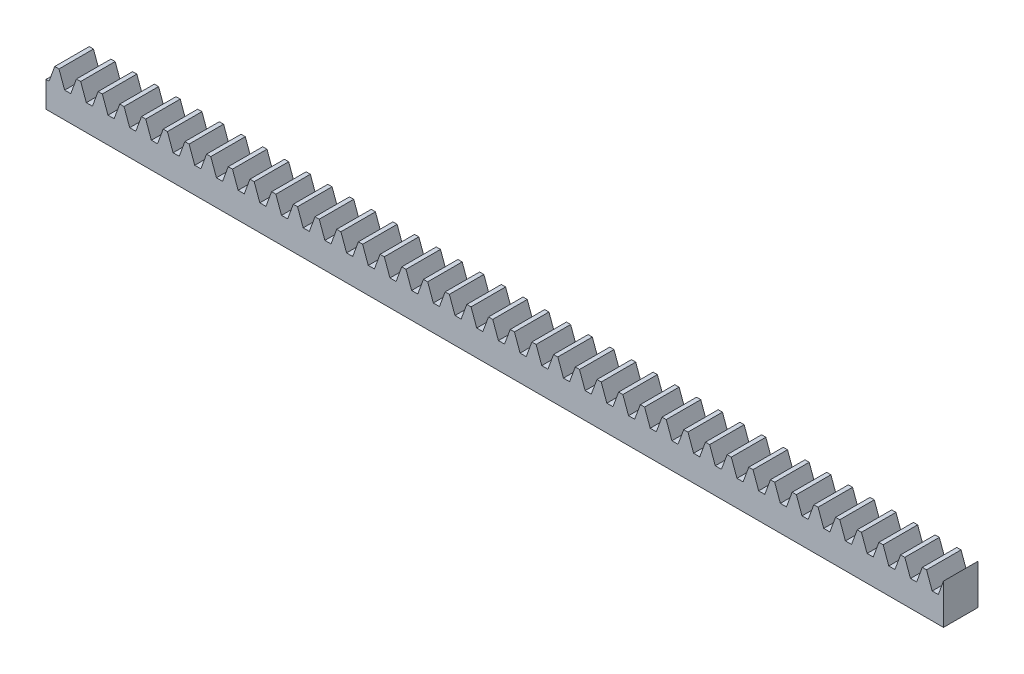
SolidWorks part; units mm, degrees
extrude "Blank" add sketch "BlankSke" against normal blind 5
sketch "BlankSke" plane through (0, 0, 0) normal (0, 0, 1) x (1, 0, 0)
  line L1 (0, 0) -> (130, 0)
  line L2 (0, 0) -> (0, 6)
  line L3 (0, 6) -> (130, 6)
  line L4 (130, 0) -> (130, 6)
  dimension "Length" = 130
  dimension "Blank_height" = 6
ref_plane "Plane1" through (0, 0, 0) normal (0, 0, 1) x (1, 0, 0)
ref_plane "Plane2" through (0, 0, 0) normal (0, 1, 0) x (1, 0, 0)
ref_plane "Plane3" through (0, 0, 0) normal (1, 0, 0) x (0, 0, -1)
sketch "HoldingSke" plane through (0, 0, 0) normal (0, 1, 0) x (1, 0, 0)
  line L0 (0, 0) -> (0.1392, 0.9903)
  line L1 (-15, 0) -> (100, 0) construction
  line L2 (0, 0) -> (-2.1039, 2.3779)
  line L3 (0, 0) -> (-11.863, 4.5341)
  line L4 (0, 0) -> (6.316, 5.8897)
  line L5 (0, 0) -> (-23.7986, -8.8762)
  line L6 (0, 0) -> (-10.5278, -7.1032)
  line L9 (-71.009, 38.7566) -> (51.1511, 83.2192)
  line L10 (-76.2, 3.3779) -> (-71.2, 3.3779)
  line L11 (0, 0) -> (-5, 0)
  line L12 (-76.2, 101.6) -> (-76.162, 101.6)
  line L13 (24.9733, 27.94) -> (52.9518, 28.4284)
  line L14 (24.9733, 27.94) -> (24.9743, 27.94)
  line L15 (24.9733, 27.94) -> (100.4006, 29.5858)
  circle A0 centre (0, 0) radius 19.05
  circle A1 centre (0, 0) radius 2.5
  circle A2 centre (0, 0) radius 12.7
  dimension "MPH" = 5
  dimension "Diameter" = 38.1
  dimension "Num_teeth" = 43
  dimension "Pitch" = 1
  dimension "Show_teeth" = 998
  dimension "Thickness" = 12.7
  dimension "Ap" = 20
  dimension "Pitch_height" = 5
  dimension "Width" = 5
  dimension "Backlash" = 0.038
  dimension "Addendum_fac" = 1
  dimension "Dedendum_fac" = 1.25
  dimension "Clearance_fac" = 0.25
  dimension "Dedendum_add" = 0.001
  dimension "Length" = 130
  dimension "Module" = 1
sketch "TooCutSkeIll" plane through (0, 0, 0) normal (0, 0, 1) x (1, 0, 0)
  line L0 (-1.2538, 5.9737) -> (-0.5045, 3.9152)
  line L1 (-0.2687, 3.75) -> (0.2687, 3.75)
  line L2 (0.5045, 3.9152) -> (1.2538, 5.9737)
  line L3 (130, 6) -> (0, 6) construction
  line L4 (0, 0) -> (0, 64.897) construction
  line L5 (-13.208, 5) -> (12.954, 5) construction
  line L6 (0, 0) -> (130, 0) construction
  line L7 (0.8994, 5) -> (0.8994, 48.7463) construction
  line L8 (-0.8994, 5) -> (-0.8994, 48.7463) construction
  line L9 (1.2914, 6) -> (1.2914, 6.0254)
  line L10 (-1.2914, 6) -> (-1.2914, 6.0254)
  line L11 (-1.2914, 6.0254) -> (1.2914, 6.0254)
  arc A0 (0.2687, 3.75) -> (0.5045, 3.9152) centre (0.2687, 4.001) ccw
  arc A1 (-0.5045, 3.9152) -> (-0.2687, 3.75) centre (-0.2687, 4.001) ccw
  arc A2 (1.2914, 6) -> (1.2538, 5.9737) centre (1.2914, 5.96) ccw
  arc A3 (-1.2538, 5.9737) -> (-1.2914, 6) centre (-1.2914, 5.96) ccw
  dimension "Pitch_height" = 5
  dimension "Addendum_plus" = 1.0254
  dimension "Pressure_angle" = 20
  dimension "Gap_width" = 1.7988
  dimension "Dedendum" = 1.25
extrude "ToothCutIll" [suppressed] cut sketch "TooCutSkeIll" against normal through all
sketch "TooCutSkeSim" plane through (0, 0, 0) normal (0, 0, 1) x (1, 0, 0)
  line L0 (0.4444, 3.75) -> (-0.4444, 3.75)
  line L1 (1.2726, 6.0254) -> (0.4444, 3.75)
  line L2 (0, 17.4625) -> (0, 53.467) construction
  line L3 (1.2726, 6.0254) -> (-1.2726, 6.0254)
  line L6 (-1.2726, 6.0254) -> (-0.4444, 3.75)
  line L9 (-0.8994, 5) -> (0.8994, 5) construction
  line L10 (0, 0) -> (130, 0) construction
  line L11 (0.8994, 5) -> (0.8994, 53.467) construction
  line L12 (-0.8994, 5) -> (-0.8994, 53.467) construction
  dimension "Pitch_height" = 5
  dimension "Addendum_plus" = 1.0254
  dimension "Pressure_angle" = 20
  dimension "Gap_width" = 1.7988
  dimension "Dedendum" = 1.25
extrude "ToothCutSim" cut sketch "TooCutSkeSim" against normal through all
pattern_linear "TeethCuts" count 42 spacing 3.1416 along (1, 0, 0) of "ToothCutIll", "ToothCutSim"
equation "' \"Module@HoldingSke\" = 6.35"
equation "' \"Num_teeth@HoldingSke\" = 12"
equation "' \"Ap@HoldingSke\" =  20"
equation "' \"Ap@HoldingSke\" = 20"
equation "' \"Width@HoldingSke\" = 0.25 * 25.4"
equation "' \"Show_teeth@HoldingSke\" = 500"
equation "' \"Backlash@HoldingSke\" = 0.009 * 25.4"
equation "' \"Addendum_fac@HoldingSke\" = 1.0"
equation "' \"Dedendum_fac@HoldingSke\" = 1.25"
equation "' \"Dedendum_add@HoldingSke\" = 0.00005 * 25.4"
equation "' \"Clearance_fac@HoldingSke\" = 0.25"
equation "' \"Pitch_height@HoldingSke\" = 1 * 25.4"
equation "' \"Length@HoldingSke\" = 4.71 * 25.4"
equation "\"Pitch@HoldingSke\" = 1 / \"Module@HoldingSke\""
equation "\"MPH@HoldingSke\" = \"Dedendum_fac@HoldingSke\" / \"Pitch@HoldingSke\" + 2 * \"Dedendum_add@HoldingSke\" + 0.002 * 25.4"
equation "\"MPH@HoldingSke\" = ((sgn( \"MPH@HoldingSke\" - \"Pitch_height@HoldingSke\")+1)*( \"MPH@HoldingSke\" - \"Pitch_height@HoldingSke\"))/2 + \"Pitch_height@HoldingSke\""
equation "\"Blank_height@BlankSke\" = \"Pitch_height@HoldingSke\" + \"Addendum_fac@HoldingSke\"  / \"Pitch@HoldingSke\" "
equation "\"Length@BlankSke\" =  \"Length@HoldingSke\""
equation "\"Face_width@Blank\" = \"Width@HoldingSke\""
equation "\"Pressure_angle@TooCutSkeIll\" = \"Ap@HoldingSke\""
equation "\"Addendum_plus@TooCutSkeIll\" =  \"Addendum_fac@HoldingSke\"  / \"Pitch@HoldingSke\" + 0.001 *25.4"
equation "\"Dedendum@TooCutSkeIll\" = \"Dedendum_fac@HoldingSke\"  / \"Pitch@HoldingSke\""
equation "\"Pitch_height@TooCutSkeIll\" =  \"MPH@HoldingSke\""
equation "\"Gap_width@TooCutSkeIll\" = 3.14159265 / 2 / \"Pitch@HoldingSke\" + 6 * \"Backlash@HoldingSke\""
equation "\"Pressure_angle@TooCutSkeSim\" = \"Ap@HoldingSke\""
equation "\"Addendum_plus@TooCutSkeSim\" =  \"Addendum_fac@HoldingSke\"  / \"Pitch@HoldingSke\" + 0.001 * 25.4"
equation "\"Dedendum@TooCutSkeSim\" = \"Dedendum_fac@HoldingSke\"  / \"Pitch@HoldingSke\""
equation "\"Pitch_height@TooCutSkeSim\" =  \"MPH@HoldingSke\""
equation "\"Gap_width@TooCutSkeSim\" = 3.14159265 / 2 / \"Pitch@HoldingSke\" + 6 * \"Backlash@HoldingSke\""
equation "\"Root_fillet@TooCutSkeIll\" = \"Clearance_fac@HoldingSke\" / \"Pitch@HoldingSke\" + \"Dedendum_add@HoldingSke\""
equation "\"Break_rad@TooCutSkeIll\" = 0.02 / \"Pitch@HoldingSke\" * 2"
equation "\"Linear_pitch@TeethCuts\" = 3.14159265 / \"Pitch@HoldingSke\""
equation "\"Num_teeth@HoldingSke\" = int( ( \"Length@HoldingSke\" + 0 ) / (3.14159265 / \"Pitch@HoldingSke\")) + 0.9999  + 1"
equation " \"Num_teeth@TeethCuts\" = int( \"Show_teeth@HoldingSke\" ) + 1"
equation " \"Num_teeth@TeethCuts\" = ((sgn( \"Num_teeth@TeethCuts\" - \"Num_teeth@HoldingSke\" )-1)*( \"Num_teeth@TeethCuts\" - \"Num_teeth@HoldingSke\" ))/-2+ \"Num_teeth@HoldingSke\""
equation " \"Num_teeth@TeethCuts\" = ((sgn( \"Num_teeth@TeethCuts\" - 2.0)+1)*( \"Num_teeth@TeethCuts\" - 2.0))/2 +2.0"
